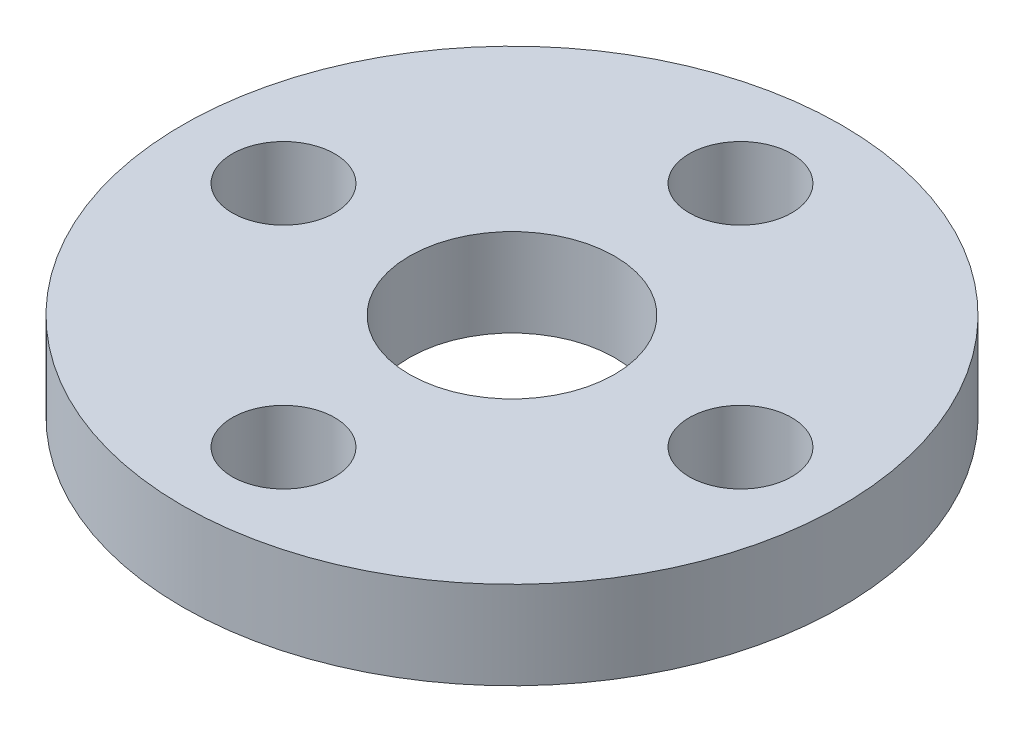
SolidWorks part; units mm, degrees
ref_plane "Front Plane" through (0, 0, 0) normal (0, 0, 1) x (1, 0, 0)
ref_plane "Top Plane" through (0, 0, 0) normal (0, 1, 0) x (1, 0, 0)
ref_plane "Right Plane" through (0, 0, 0) normal (1, 0, 0) x (0, 0, -1)
sketch "Sketch1" plane through (0, 0, 0) normal (0, 1, 0) x (1, 0, 0)
  circle A0 centre (0, 0) radius 11.25
  dimension "D1" = 22.5
extrude "Boss-Extrude1" add sketch "Sketch1" along normal blind 3
sketch "Sketch2" plane through (0, 3, 0) normal (0, 1, 0) x (1, 0, 0)
  circle A0 centre (0, 0) radius 7.8 construction
  circle A1 centre (0, 7.8) radius 1.75
  circle A2 centre (7.8, 0) radius 1.75
  circle A3 centre (0, -7.8) radius 1.75
  circle A4 centre (-7.8, 0) radius 1.75
  circle A5 centre (0, 0) radius 3.5
  dimension "D1" = 15.6
  dimension "D2" = 3.5
  dimension "D3" = 7
extrude "Cut-Extrude1" cut sketch "Sketch2" against normal up to next
